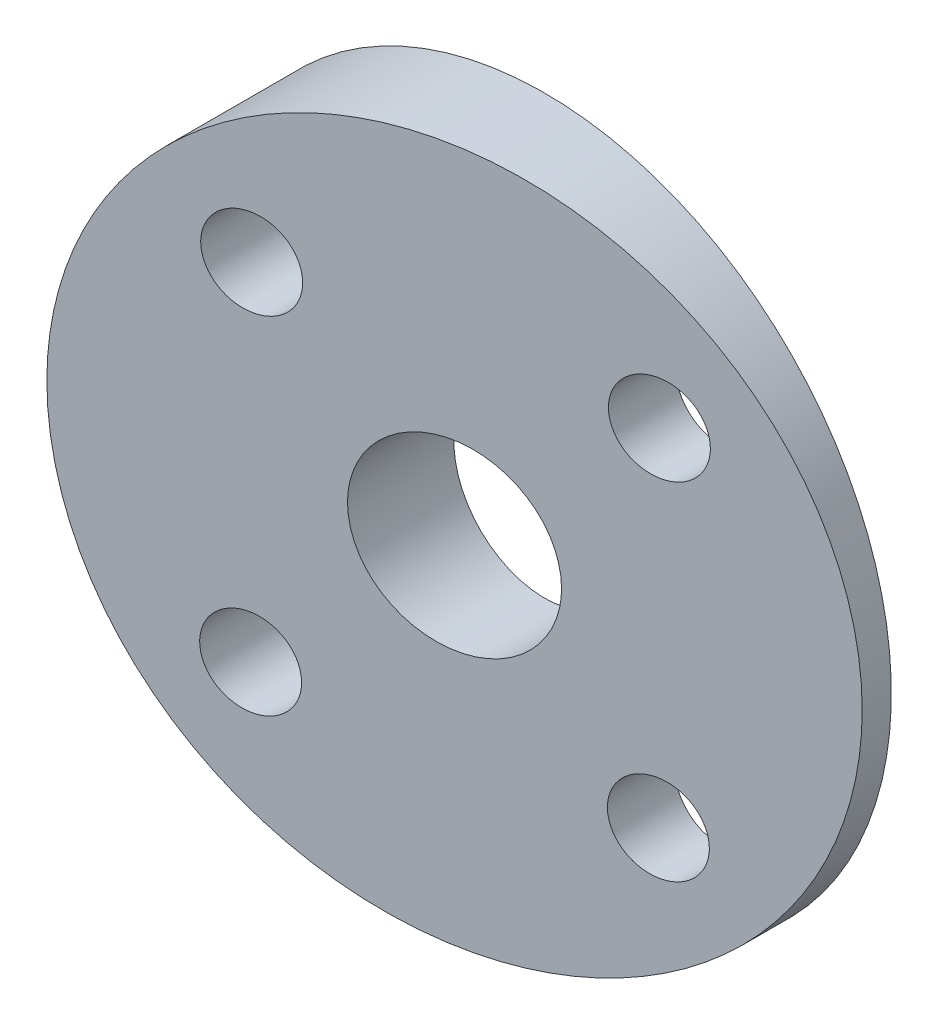
SolidWorks part; units mm, degrees
ref_plane "Front" through (0, 0, 0) normal (0, 0, 1) x (1, 0, 0)
ref_plane "Top" through (0, 0, 0) normal (0, 1, 0) x (1, 0, 0)
ref_plane "Right" through (0, 0, 0) normal (1, 0, 0) x (0, 0, -1)
sketch "Sketch1" plane through (0, 0, 0) normal (0, 1, 0) x (1, 0, 0)
  line L2 (0, 0) -> (0, -29)
  line L3 (0, -29) -> (10, -29)
  line L4 (10, 0) -> (10, -29)
  line L5 (10, 0) -> (-31.85, 0)
  line L6 (10, 0) -> (10, 10)
  line L7 (10, 10) -> (-31.85, 10)
  line L8 (-31.85, 0) -> (-31.85, 10)
  dimension "D1" = 41.85
  dimension "D2" = 29
  dimension "D3" = 10
  dimension "D4" = 10
extrude "Boss-Extrude1" add sketch "Sketch1" along normal blind 48 contours L8 L5 L6 L7 | L4 L5 L2 L3
sketch "Sketch4" plane through (0, 0, 0) normal (0, 0, 1) x (1, 0, 0)
  circle A0 centre (-5.5896, 40.9808) radius 2
  circle A1 centre (-5.6297, 24.9791) radius 2
  circle A2 centre (-21.5913, 41.0209) radius 2
  circle A3 centre (-21.6315, 25.0192) radius 2
  circle A4 centre (-13.6297, 32.9791) radius 4.2
extrude "Cut-Extrude2" cut sketch "Sketch4" against normal blind 48
sketch "Sketch7" plane through (0, 0, 0) normal (0, -1, 0) x (1, 0, 0)
  line L1 (34.0187, -20.7683) -> (-66.3079, -20.7683)
  line L2 (34.0187, -20.7683) -> (34.0187, 36.3754)
  line L3 (34.0187, 36.3754) -> (-66.3079, 36.3754)
  line L4 (-66.3079, -20.7683) -> (-66.3079, 36.3754)
extrude "Cut-Extrude5" cut sketch "Sketch7" against normal blind 14.7
sketch "Sketch8" plane through (0, 14.7, 0) normal (0, -1, 0) x (1, 0, 0)
  line L0 (10, -10) -> (-31.85, -2.6207)
  line L1 (-31.85, -10) -> (-31.85, 0) construction
  line L2 (-31.85, -2.6207) -> (-31.85, -10)
  line L3 (-31.85, -10) -> (10, -10) construction
  line L4 (-31.85, -10) -> (10, -10)
  line L5 (10, -10) -> (10, 29)
  line L6 (10, 29) -> (0, 29)
  line L7 (0, 29) -> (0, 0)
  line L8 (0, 0) -> (-31.85, 0)
  line L9 (-31.85, 0) -> (-31.85, -2.6207)
  line M4 (10, -10) -> (10, 29)
  line M5 (10, 29) -> (0, 29)
  line M6 (0, 29) -> (0, 0)
  line M7 (0, 0) -> (-31.85, 0)
  line M8 (-31.85, 0) -> (-31.85, -10)
  dimension "D1" = 10
extrude "Cut-Extrude6" cut sketch "Sketch8" against normal blind 54.7 contours L0 M4 M5 M6 M7 M8
sketch "Sketch18" plane through (0, 48, 0) normal (0, 1, 0) x (1, 0, 0)
  line L0 (-31.85, 2.6207) -> (-31.85, 10)
  line L1 (-31.85, 10) -> (10, 10)
  line L2 (10, 10) -> (-31.85, 2.6207)
extrude "Boss-Extrude5" add sketch "Sketch18" along normal blind 13.7
sketch "Sketch19" plane through (0, 0, -10) normal (0, 0, -1) x (-1, 0, 0)
  line L1 (40.4128, 86.452) -> (-14.8355, 86.452)
  line L2 (40.4128, 86.452) -> (40.4128, 0)
  line L3 (40.4128, 0) -> (-14.8355, 0)
  line L4 (-14.8355, 86.452) -> (-14.8355, 0)
  circle A0 centre (13.6297, 32.9791) radius 16
extrude "Cut-Extrude10" cut sketch "Sketch19" against normal blind 13.7
